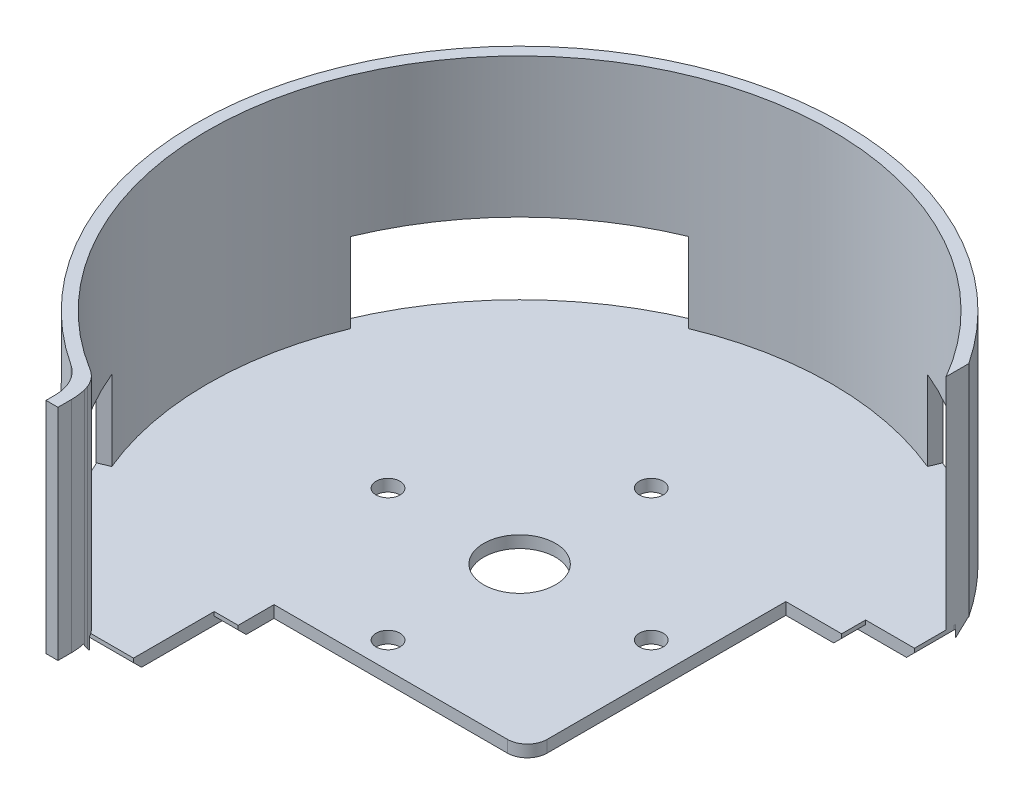
SolidWorks part; units mm, degrees
ref_plane "Front Plane" through (0, 0, 0) normal (0, 0, 1) x (1, 0, 0)
ref_plane "Top Plane" through (0, 0, 0) normal (0, 1, 0) x (1, 0, 0)
ref_plane "Right Plane" through (0, 0, 0) normal (1, 0, 0) x (0, 0, -1)
sketch "Sketch1" plane through (0, 0, 0) normal (0, 1, 0) x (1, 0, 0)
  line L0 (26.0161, -39.5914) -> (36.5161, -39.5914)
  line L1 (-21.9839, -39.5914) -> (26.0161, -39.5914)
  line L3 (-21.9839, -39.5914) -> (-21.9839, -48.5914)
  line L4 (41.5161, -34.5914) -> (41.5161, -22.7641)
  line L5 (-27.9839, -68.8289) -> (-39.9277, -68.8289)
  line L6 (67.7732, 31.2359) -> (67.7732, 41.6944)
  line L10 (41.5161, -22.7641) -> (41.5161, 25.2359)
  line L11 (41.5161, 25.2359) -> (55.5161, 25.2359)
  line L12 (-38.8113, 23.9086) -> (-68.0487, 23.9086) [skipped]
  line L13 (-38.8113, 23.9086) -> (-38.8113, -24.0914) [skipped]
  line L16 (24.6887, 40.7359) -> (-23.3113, 40.7359) [skipped]
  line L17 (24.6887, 40.7359) -> (24.6887, 69.9734) [skipped]
  line L18 (41.5161, -22.7641) -> (70.7535, -22.7641) [skipped]
  line L27 (-21.9839, -48.5914) -> (-27.9839, -48.5914)
  line L28 (67.7732, 25.2359) -> (67.7732, 43.9086) construction
  line L29 (-21.9839, -68.8289) -> (-41.9839, -68.8289) construction
  line L30 (-27.9839, -48.5914) -> (-27.9839, -68.8289)
  line L31 (55.5161, 25.2359) -> (55.5161, 31.2359)
  line L32 (-21.9839, -39.5914) -> (-21.9839, -68.8289) construction
  line L33 (55.5161, 31.2359) -> (67.7732, 31.2359)
  line L35 (41.5161, 25.2359) -> (67.7732, 25.2359) construction
  line L38 (77.7732, 43.9086) -> (78.0711, 43.9086)
  line L47 (26.0161, -26.5914) -> (28.5161, -26.5914)
  line L48 (28.5161, -26.5914) -> (28.5161, -22.7641)
  line L89 (-34.9839, -55.8289) -> (-52.4056, -55.8289) construction
  line L90 (-34.9839, -26.5914) -> (-34.9839, -55.8289) construction
  line L91 (-34.9839, -26.5914) -> (26.0161, -26.5914) construction
  line L92 (28.5161, -22.7641) -> (28.5161, 38.2359) construction
  line L93 (54.7732, 38.2359) -> (54.7732, 53.5079) construction
  line L94 (28.5161, 38.2359) -> (54.7732, 38.2359) construction
  line L95 (54.7732, 53.5079) -> (54.7732, 53.5079) construction
  line L96 (54.7732, 53.5079) -> (54.7732, 53.5079) construction
  line L97 (-52.4056, -55.8289) -> (-52.4056, -55.8289) construction
  line L98 (-52.4056, -55.8289) -> (-52.4056, -55.8289) construction
  line L99 (-52.4056, -55.8289) -> (-52.4056, -55.8289) construction
  line L100 (67.7732, 43.9086) -> (77.7732, 43.9086) construction
  line L101 (-41.9839, -68.8289) -> (-41.9839, -78.8289) construction
  line L102 (-41.9839, -77.7316) -> (-41.9839, -87.6815) construction
  line L103 (-41.9839, -78.8289) -> (-41.9839, -77.7316) construction
  circle A2 centre (0, 0) radius 9
  circle A4 centre (33, 0) radius 3
  circle A8 centre (0, -33) radius 3
  circle A9 centre (-33, 0) radius 3
  circle A10 centre (0, 33) radius 3
  arc A11 (41.5161, -34.5914) -> (36.5161, -39.5914) centre (36.5161, -34.5914) cw
  arc A15 (67.7732, 41.6944) -> (-39.9277, -68.8289) centre (0, 0) ccw
  arc A16 (28.5161, -26.5914) -> (28.5161, -26.5914) centre (28.5161, -26.5914) cw
  arc A23 (54.7732, 53.5079) -> (-52.4056, -55.8289) centre (0, 0) ccw construction
  arc A28 (-52.4056, -55.8289) -> (-52.4056, -55.8289) centre (-52.4056, -55.8289) cw construction
  arc A29 (78.0711, 43.9086) -> (-48.81, -75.1042) centre (0, 0) ccw construction
  arc A30 (-41.9839, -87.6815) -> (-48.81, -75.1042) centre (-56.9839, -87.6815) ccw construction
  point P8 (2.0161, -39.5914)
  point P21 (1.3524, 0.5723)
  point P29 (78.2165, 43.6491)
  point P36 (0, 0)
  point P37 (0, 0)
  point P38 (-41.7244, -79.2599)
  point P40 (70.4285, 37.0332)
  point P41 (-34.8674, -71.5255)
  point P53 (-41.9839, -79.2073)
  point P74 (-38.9839, -87.6815)
  point P76 (-56.9839, -87.6815)
  point P77 (-47.1752, -72.5888)
  dimension "D1" = 5
  dimension "D4" = 18
  dimension "D5" = 33
  dimension "D6" = 6
  dimension "D2" = 4
  dimension "D3" = 48
  dimension "D7" = 4
  dimension "D8" = 9
  dimension "D9" = 6
  dimension "D10" = 14
  dimension "D11" = 6
  dimension "D12" = 13
extrude "Boss-Extrude1" add sketch "Sketch1" along normal blind 3
ref_plane "Plane2" through (0, 23, 0) normal (0, 1, 0) x (1, 0, 0)
sketch "Sketch2" plane through (0, 3, 0) normal (0, 1, 0) x (1, 0, 0)
  line L0 (67.7732, 31.2359) -> (67.7732, 41.6944) construction
  line L1 (67.7732, 39.1565) -> (67.7732, 44.8538)
  line L2 (-27.9839, -68.8289) -> (-39.9277, -68.8289) construction
  line L3 (-33.5528, -68.8289) -> (-38.702, -68.8289)
  line L4 (-39.9277, -76.9852) -> (-39.9277, -78.8289)
  line L5 (-36.9277, -75.4246) -> (-36.9277, -78.8289)
  line L6 (-36.9277, -68.8289) -> (-36.9277, -78.8289) construction
  line L7 (-39.9277, -78.8289) -> (-36.9277, -78.8289)
  line L8 (-39.9277, -68.8289) -> (-39.9277, -78.8289) construction
  line L9 (0, 0) -> (99.5795, 0)
  line L10 (55.3463, 55.3463) -> (57.4677, 57.4677)
  line L11 (29.9532, 72.3135) -> (31.1013, 75.0851)
  line L13 (-29.9532, 72.3135) -> (-31.1013, 75.0851)
  line L17 (-72.3135, -29.9532) -> (-75.0851, -31.1013)
  line L18 (-55.3463, -55.3463) -> (-57.4677, -57.4677)
  line L21 (-70.7429, 29.3027) -> (-73.5145, 30.4507) construction
  line L22 (-70.7429, -29.3027) -> (-73.5145, -30.4507) construction
  line L23 (-68.7692, -30.1087) -> (-74.3135, -32.4053) construction
  line L24 (-72.3135, 29.9532) -> (-75.0851, 31.1013)
  line L25 (-68.7692, 30.1087) -> (-74.3135, 32.4053) construction
  arc A5 (-39.9277, -76.9852) -> (-40.0376, -75.1726) centre (-54.9277, -76.9852) ccw
  arc A6 (-36.9277, -75.4246) -> (-37.3891, -71.7327) centre (-51.9277, -75.4246) ccw
  arc A14 (-68.7692, 30.1087) -> (-69.3571, 28.7286) centre (0, 0) ccw
  arc A15 (-73.5145, 30.4507) -> (-73.5145, -30.4507) centre (0, 0) ccw construction
  arc A17 (-74.3135, 32.4053) -> (-74.3135, -32.4053) centre (0, 0) ccw construction
  arc A18 (-68.7692, 30.1087) -> (-68.7692, -30.1087) centre (0, 0) ccw construction
  arc A20 (-70.7429, 29.3027) -> (-70.7429, -29.3027) centre (0, 0) ccw construction
  arc A28 (-41.023, -66.6599) -> (-37.7536, -70.5899) centre (-45.2159, -73.4731) cw
  arc A34 (67.7732, 39.1565) -> (55.3463, 55.3463) centre (0, 0) ccw
  arc A40 (-37.7536, -70.5899) -> (-37.3891, -71.7327) centre (-47.0815, -74.1939) cw
  arc A41 (-44.4901, -68.0125) -> (-40.0376, -75.1726) centre (-49.9644, -76.381) cw
  arc A42 (-57.4677, -57.4677) -> (-44.4901, -68.0125) centre (0, 0) ccw
  arc A43 (-55.3463, -55.3463) -> (-41.023, -66.6599) centre (0, 0) ccw
  arc A44 (67.7732, 44.8538) -> (57.4677, 57.4677) centre (0, 0) ccw
  arc A45 (69.2211, 42.5852) -> (-40.7807, -70.2993) centre (0, 0) ccw construction
  arc A46 (-72.3135, 29.9532) -> (-72.3135, -29.9532) centre (0, 0) ccw
  arc A47 (66.666, 41.0133) -> (-39.2754, -67.7044) centre (0, 0) ccw construction
  arc A48 (-75.0851, 31.1013) -> (-75.0851, -31.1013) centre (0, 0) ccw
  arc A49 (29.9532, 72.3135) -> (-29.9532, 72.3135) centre (0, 0) ccw
  arc A50 (31.1013, 75.0851) -> (-31.1013, 75.0851) centre (0, 0) ccw
  point P29 (-39.4068, -67.1646)
  line M12 (67.7732, 31.2359) -> (67.7732, 41.6944)
  arc M13 (67.7732, 41.6944) -> (-39.9277, -68.8289) centre (0, 0) ccw
  line M14 (-39.9277, -68.8289) -> (-27.9839, -68.8289)
  dimension "D4" = 15
  dimension "D5" = 15
  dimension "D13" = 10
  dimension "D8" = 8
  dimension "D2" = 10
  dimension "D6" = 45
  dimension "D7" = 22.5
  dimension "D9" = 1.5
  dimension "D12" = 22.5
  dimension "D3" = 3
  dimension "D14" = 3
extrude "Boss-Extrude5" add sketch "Sketch2" along normal blind 20 contours L18 A42 A41 A5 L4 L7 L5 A6 A40 A28 M14 M13 | A43 L18 A28 M13 M14 | A46 L24 L17 M13 | L11 A50 L13 M13 | A49 L11 L13 M13 | L1 A44 L10 M13 | A34 L10 M12 M13
chamfer "Chamfer1" distance 2 angle 45 1 edges at (67.7732, 0, -36.4652)
chamfer "Chamfer2" distance 2 angle 45 1 edges at (55.5161, 0, -28.2359)
chamfer "Chamfer3" distance 2 angle 45 1 edges at (-33.9558, 0, 68.8289)
chamfer "Chamfer4" distance 2 angle 45 1 edges at (-24.9839, 0, 48.5914)
fillet "Fillet3" radius 2 1 edges at (67.7732, 2.5, -41.6944)
sketch "Sketch3" plane through (0, 23, 0) normal (0, 1, 0) x (1, 0, 0)
  line L0 (67.7732, 39.1565) -> (67.7732, 44.8538) construction
  line L1 (67.7732, 39.1565) -> (67.7732, 44.8538)
  line L2 (-39.9277, -76.9852) -> (-39.9277, -78.8289) construction
  line L3 (-39.9277, -76.9852) -> (-39.9277, -78.8289)
  line L4 (-39.9277, -78.8289) -> (-36.9277, -78.8289) construction
  line L5 (-39.9277, -78.8289) -> (-36.9277, -78.8289)
  line L6 (-36.9277, -75.4246) -> (-36.9277, -78.8289) construction
  line L7 (-36.9277, -75.4246) -> (-36.9277, -78.8289)
  arc A0 (67.7732, 44.8538) -> (-44.4901, -68.0125) centre (0, 0) ccw
  arc A1 (67.7732, 39.1565) -> (-41.023, -66.6599) centre (0, 0) ccw
  arc A2 (-40.0376, -75.1726) -> (-44.4901, -68.0125) centre (-49.9644, -76.381) ccw construction
  arc A3 (-40.0376, -75.1726) -> (-44.4901, -68.0125) centre (-49.9644, -76.381) ccw
  arc A4 (-39.9277, -76.9852) -> (-40.0376, -75.1726) centre (-54.9277, -76.9852) ccw construction
  arc A5 (-39.9277, -76.9852) -> (-40.0376, -75.1726) centre (-54.9277, -76.9852) ccw
  arc A6 (-36.9277, -75.4246) -> (-37.3891, -71.7327) centre (-51.9277, -75.4246) ccw construction
  arc A7 (-36.9277, -75.4246) -> (-37.3891, -71.7327) centre (-51.9277, -75.4246) ccw
  arc A8 (-37.3891, -71.7327) -> (-37.7536, -70.5899) centre (-47.0815, -74.1939) ccw construction
  arc A9 (-37.3891, -71.7327) -> (-37.7536, -70.5899) centre (-47.0815, -74.1939) ccw
  arc A10 (-37.7536, -70.5899) -> (-41.023, -66.6599) centre (-45.2159, -73.4731) ccw construction
  arc A11 (-37.7536, -70.5899) -> (-41.023, -66.6599) centre (-45.2159, -73.4731) ccw
extrude "Boss-Extrude6" add sketch "Sketch3" along normal blind 35
sketch "Sketch4" plane through (0, 0, 0) normal (1, 0, 0) x (0, 0, -1)
  line L0 (79.4489, 0) -> (81.1782, 3)
  line L1 (-66.8289, 0) -> (79.5716, 0) construction
  line L2 (75.0851, 3) -> (81.2716, 3) construction
  line L3 (81.1782, 3) -> (79.4489, 3)
  line L4 (73.5145, 3) -> (79.5716, 3) construction
  line L5 (79.4489, 3) -> (79.4489, 0)
  line L6 (0, 0) -> (0, -37.702) construction
revolve "Revolve1" add sketch "Sketch4" angle 360 about L6
sketch "Sketch5" plane through (0, 3, 0) normal (0, 1, 0) x (1, 0, 0)
  line L0 (67.7732, 44.6844) -> (67.7732, 41.4599) construction
  line L1 (67.7732, 44.6844) -> (67.7732, 41.4599)
  arc A0 (-37.7536, -70.5899) -> (-38.174, -69.677) centre (-45.2159, -73.4731) ccw construction
  arc A1 (-37.3891, -71.7327) -> (-37.7536, -70.5899) centre (-47.0815, -74.1939) ccw construction
  arc A2 (-37.3005, -72.1012) -> (-37.3891, -71.7327) centre (-51.9277, -75.4246) ccw construction
  arc A3 (-37.7536, -70.5899) -> (-38.174, -69.677) centre (-45.2159, -73.4731) ccw
  arc A4 (-37.3891, -71.7327) -> (-37.7536, -70.5899) centre (-47.0815, -74.1939) ccw
  arc A5 (-37.3005, -72.1012) -> (-37.3891, -71.7327) centre (-51.9277, -75.4246) ccw
  arc A6 (-38.174, -69.677) -> (67.7732, 41.4599) centre (0, 0) ccw construction
  arc A7 (-38.174, -69.677) -> (67.7732, 41.4599) centre (0, 0) ccw
  arc A8 (-37.3005, -72.1012) -> (67.7732, 44.6844) centre (0, 0) ccw construction
  arc A9 (-37.3005, -72.1012) -> (67.7732, 44.6844) centre (0, 0) ccw
extrude "Cut-Extrude1" cut sketch "Sketch5" against normal blind 35
ref_plane "Plane1" through (0, 20, 0) normal (0, 1, 0) x (1, 0, 0)
